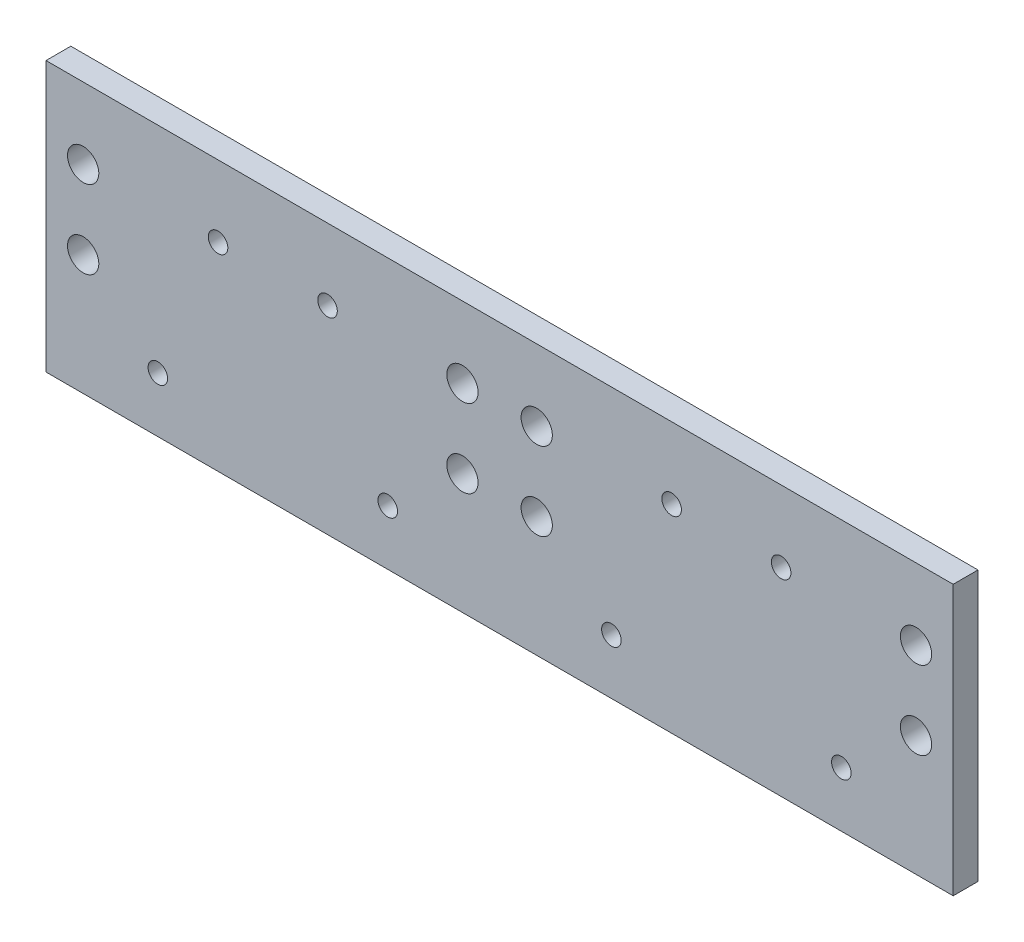
SolidWorks part; units mm, degrees
material "Plain Carbon Steel"
ref_plane "Front" through (0, 0, 0) normal (0, 0, 1) x (1, 0, 0)
ref_plane "Top" through (0, 0, 0) normal (0, 1, 0) x (1, 0, 0)
ref_plane "Right" through (0, 0, 0) normal (1, 0, 0) x (0, 0, -1)
sketch "Sketch1" plane through (0, 0, 0) normal (0, 0, 1) x (1, 0, 0)
  line L0 (29, -37.5) -> (-87, -37.5)
  line L1 (-87, -37.5) -> (-87, -3)
  line L2 (-87, -3) -> (29, -3)
  line L3 (29, -3) -> (29, -37.5)
  line L5 (29, -30) -> (29, -11) construction
  line L6 (-87, -30) -> (-87, -11) construction
  line L8 (-78.5, -3) -> (-37.5, -3) construction
  line L9 (-73, -37.5) -> (-43, -37.5) construction
  dimension "D1" = 0
  dimension "D2" = 0
  dimension "D3" = 0
  dimension "D4" = 0
extrude "Boss-Extrude1" add sketch "Sketch1" along normal blind 3.175
sketch "Sketch2" plane through (0, 0, 0) normal (0, 0, -1) x (-1, 0, 0)
  circle A0 centre (-24.25, -22.13) radius 2
  circle A1 centre (-24.25, -12.13) radius 2
  circle A2 centre (24.25, -12.13) radius 2
  circle A3 centre (24.25, -22.13) radius 2
  circle A4 centre (33.75, -12.13) radius 2
  circle A5 centre (33.75, -22.13) radius 2
  circle A6 centre (82.25, -12.13) radius 2
  circle A7 centre (82.25, -22.13) radius 2
  circle A8 centre (72.6997, -30.4497) radius 1.25
  circle A9 centre (65, -12.13) radius 1.25
  circle A10 centre (51, -12.13) radius 1.25
  circle A11 centre (43.3003, -30.4497) radius 1.25
  circle A12 centre (14.6997, -30.4497) radius 1.25
  circle A13 centre (7, -12.13) radius 1.25
  circle A14 centre (-7, -12.13) radius 1.25
  circle A15 centre (-14.6997, -30.4497) radius 1.25
extrude "Cut-Extrude1" cut sketch "Sketch2" against normal through all
